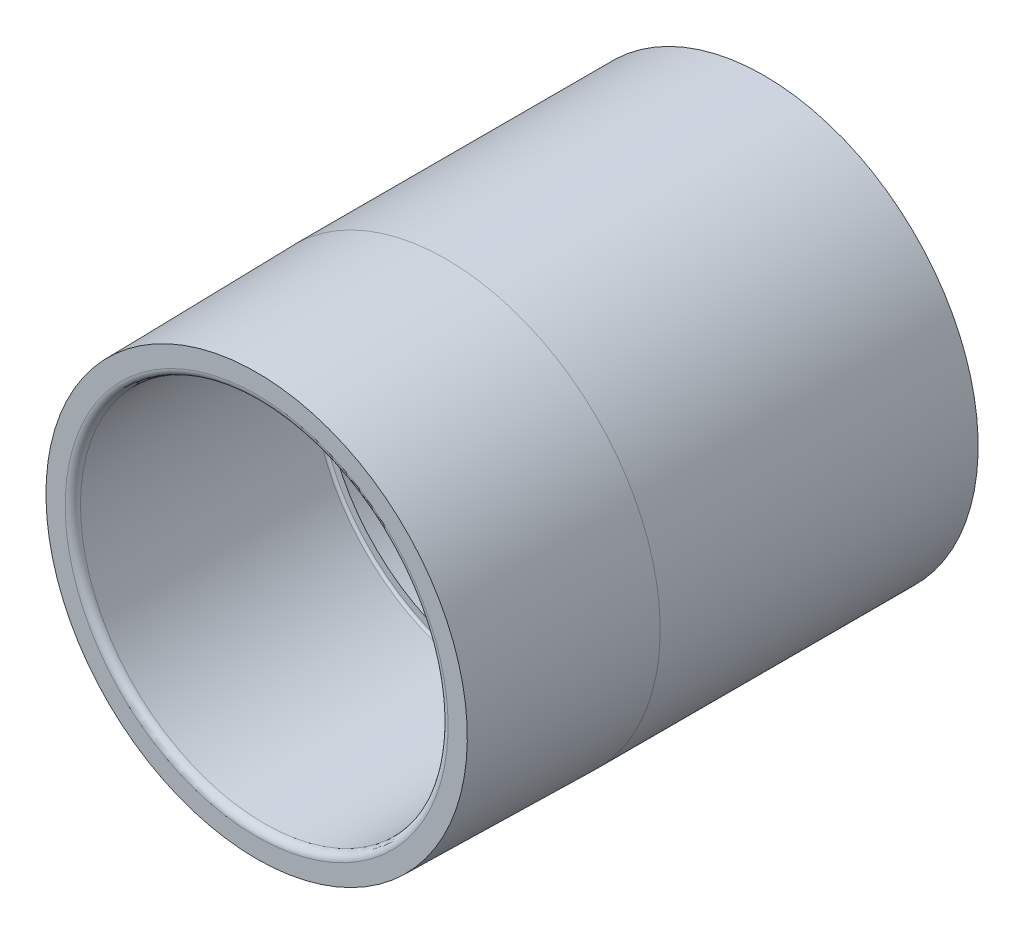
SolidWorks part; units mm, degrees
material "PVC Rigid"
ref_plane "Front Plane" through (0, 0, 0) normal (0, 0, 1) x (1, 0, 0)
ref_plane "Top Plane" through (0, 0, 0) normal (0, 1, 0) x (1, 0, 0)
ref_plane "Right Plane" through (0, 0, 0) normal (1, 0, 0) x (0, 0, -1)
sketch "Sketch1" plane through (0, 0, 0) normal (0, 0, 1) x (1, 0, 0)
  circle A0 centre (0, 0) radius 42.7101 construction
  circle A1 centre (0, 0) radius 36.6903 construction
  circle A2 centre (0, 0) radius 34.798 construction
  point P4 (-36.6903, 0)
  point P5 (0, 36.6903)
  point P6 (36.6903, 0)
  point P7 (0, -36.6903)
  point P9 (0, -34.798)
  point P10 (0, -42.7101)
  dimension "Pipe OD" = 73.3806
  dimension "Max OD" = 85.4202
  dimension "Thru ID" = 69.596
sketch "Sketch2" plane through (0, 0, 0) normal (1, 0, 0) x (0, 0, -1)
  line L0 (-50.6476, 0) -> (50.6476, 0) construction
  point P3 (0, 0)
  dimension "OAL" = 101.2952
sketch "Sketch3" plane through (0, 0, 0) normal (1, 0, 0) x (0, 0, -1)
  line L0 (-12.8133, -42.7101) -> (50.6476, -42.7101)
  line L1 (-50.6476, -42.0497) -> (-50.6476, -36.6903)
  line L2 (-50.6476, -36.6903) -> (-2.3876, -36.6903)
  line L3 (-2.3876, -36.6903) -> (-2.3876, -34.798)
  line L4 (50.6476, -42.7101) -> (50.6476, -36.6903)
  line L5 (50.6476, -36.6903) -> (2.3876, -36.6903)
  line L6 (2.3876, -36.6903) -> (2.3876, -34.798)
  line L7 (-2.3876, -34.798) -> (2.3876, -34.798)
  line L8 (-12.8133, -42.7101) -> (-50.6476, -42.0497)
  line L9 (0, 42.7101) -> (0, -42.7101) construction
  line L10 (-50.6476, 0) -> (50.6476, 0) construction
  line L11 (-2.3876, -36.6903) -> (2.3876, -36.6903) construction
  point P11 (0, -34.798)
  dimension "D1" = 42.7101
  dimension "D2" = 36.6903
  dimension "Socket Bottom Width" = 4.7752
  dimension "D3" = 34.798
  dimension "D5" = 1
  dimension "Tapered Wall Thickness" = 5.3594
  dimension "D6" = 6.0198
revolve "Revolve1" add sketch "Sketch3" angle 360 about L0
fillet "Fillet1" radius 1.524 2 edges at (0, -36.6903, -50.6476) (0, -36.6903, 50.6476)
fillet "Fillet2" radius 0.508 2 edges at (0, -36.6903, -2.3876) (0, -36.6903, 2.3876)
sketch "Sketch4" plane through (0, 0, 0) normal (1, 0, 0) x (0, 0, -1)
  line L0 (50.6476, -36.6903) -> (2.3876, -36.6903) construction
  line L1 (2.3876, -36.6903) -> (2.3876, -34.798) construction
  line L2 (-2.3876, -34.798) -> (2.3876, -34.798) construction
  line L3 (-2.3876, -36.6903) -> (-2.3876, -34.798) construction
  line L4 (-50.6476, -36.6903) -> (-2.3876, -36.6903) construction
  line L5 (49.1236, -36.6903) -> (2.8956, -36.6903)
  line L6 (2.3876, -36.1823) -> (2.3876, -34.798)
  line L7 (-2.3876, -34.798) -> (2.3876, -34.798)
  line L8 (-2.3876, -36.1823) -> (-2.3876, -34.798)
  line L9 (-49.1236, -36.6903) -> (-2.8956, -36.6903)
  line L10 (-50.6476, 0) -> (50.6476, 0) construction
  line L11 (-50.6476, 42.7101) -> (-50.6476, -42.7101) construction
  line L12 (50.6476, -42.7101) -> (50.6476, 42.7101) construction
  line L13 (49.1236, 36.6903) -> (2.8956, 36.6903)
  line L14 (2.3876, 36.1823) -> (2.3876, 34.798)
  line L15 (-2.3876, 34.798) -> (2.3876, 34.798)
  line L16 (-2.3876, 36.1823) -> (-2.3876, 34.798)
  line L17 (-49.1236, 36.6903) -> (-2.8956, 36.6903)
  line L18 (-50.6476, 38.2143) -> (-50.6476, 42.0497)
  line L19 (50.6476, 42.7101) -> (50.6476, 38.2143)
  line L20 (50.6476, -42.7101) -> (50.6476, -38.2143)
  line L21 (-50.6476, -42.0497) -> (-50.6476, -38.2143)
  arc A0 (-50.6476, -38.2143) -> (-49.1236, -36.6903) centre (-49.1236, -38.2143) cw
  arc A1 (50.6476, -38.2143) -> (49.1236, -36.6903) centre (49.1236, -38.2143) ccw
  arc A2 (50.6476, 38.2143) -> (49.1236, 36.6903) centre (49.1236, 38.2143) cw
  arc A3 (-50.6476, 38.2143) -> (-49.1236, 36.6903) centre (-49.1236, 38.2143) ccw
  arc A4 (-2.8956, 36.6903) -> (-2.3876, 36.1823) centre (-2.8956, 36.1823) cw
  arc A5 (2.8956, 36.6903) -> (2.3876, 36.1823) centre (2.8956, 36.1823) ccw
  arc A6 (2.8956, -36.6903) -> (2.3876, -36.1823) centre (2.8956, -36.1823) cw
  arc A7 (-2.3876, -36.1823) -> (-2.8956, -36.6903) centre (-2.8956, -36.1823) cw
  point P34 (50.6476, 36.6903)
  point P37 (-50.6476, 36.6903)
  point P40 (-2.3876, 36.6903)
  point P43 (2.3876, 36.6903)
  dimension "D1" = 1.524
  dimension "D2" = 0.508
equation "\"D1@Sketch3\"=\"Max OD@Sketch1\"/2"
equation "\"D2@Sketch3\"=\"Pipe OD@Sketch1\"/2"
equation "\"D3@Sketch3\"=\"Thru ID@Sketch1\"/2"
equation "\"D1@Sketch4\"=\"ID Radius@Fillet1\""
equation "\"D2@Sketch4\"=\"Socket Bottom Radius@Fillet2\""
